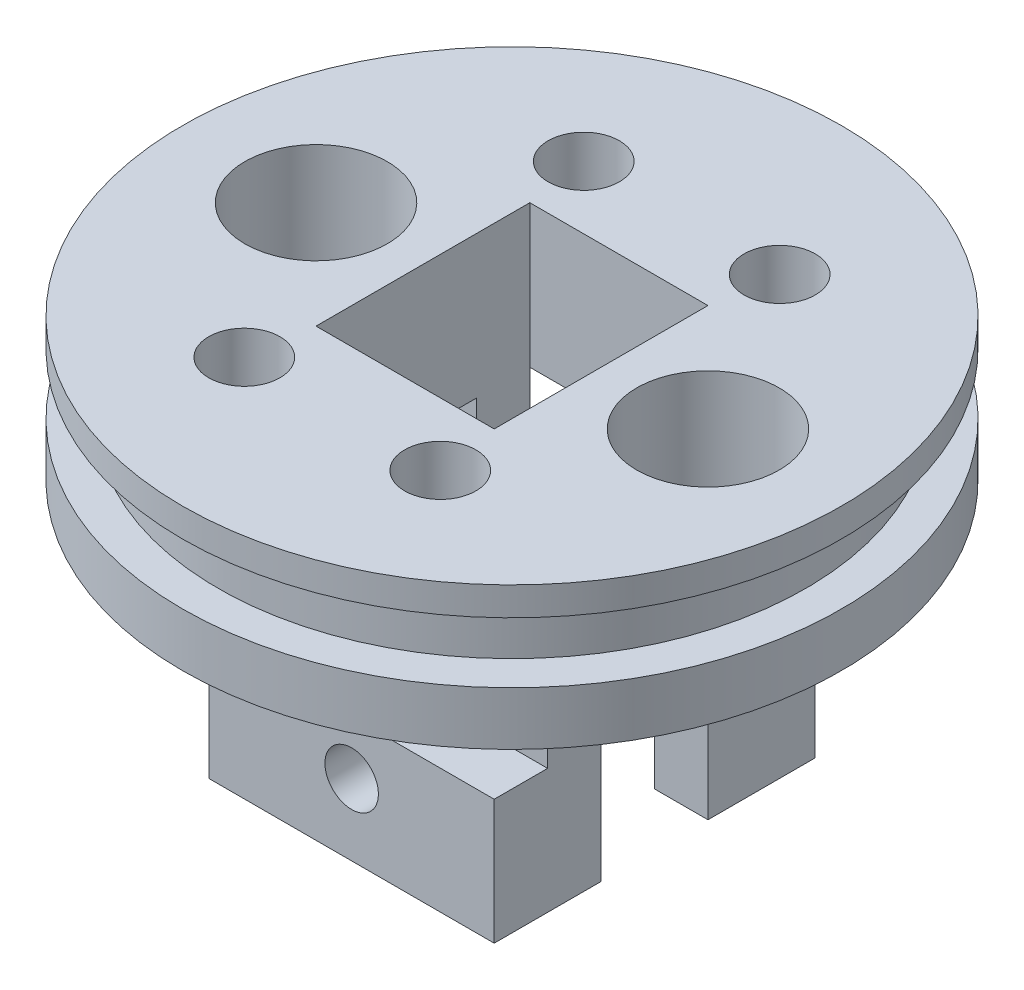
SolidWorks part; units mm, degrees
ref_plane "前视基准面" through (0, 0, 0) normal (0, 0, 1) x (1, 0, 0)
ref_plane "上视基准面" through (0, 0, 0) normal (0, 1, 0) x (1, 0, 0)
ref_plane "右视基准面" through (0, 0, 0) normal (1, 0, 0) x (0, 0, -1)
sketch "草图1" plane through (0, 0, 0) normal (0, 1, 0) x (1, 0, 0)
  circle A0 centre (0, 0) radius 11
  dimension "D1" = 22
extrude "凸台-拉伸1" add sketch "草图1" along normal blind 9
sketch "草图2" plane through (0, 9, 0) normal (0, 1, 0) x (1, 0, 0)
  circle A0 centre (-5.5, 0) radius 1
  circle A1 centre (5.5, 0) radius 1
  dimension "D1" = 2
  dimension "D2" = 2
  dimension "D3" = 11
  dimension "D4" = 5.5
extrude "切除-拉伸1" cut sketch "草图2" against normal blind 10
sketch "草图3" plane through (0, 0, 0) normal (0, -1, 0) x (1, 0, 0)
  circle A0 centre (0, 0) radius 9.25
  circle A1 centre (0, 0) radius 16.5491
  dimension "D1" = 18.5
extrude "切除-拉伸2" cut sketch "草图3" against normal blind 7
sketch "草图4" plane through (0, 0, 0) normal (0, 0, 1) x (1, 0, 0)
  line L0 (-9.25, 7) -> (-9.25, 0) construction
  line L1 (-10.25, 6.3) -> (-8.25, 6.3)
  line L2 (-10.25, 6.3) -> (-10.25, 4.6)
  line L3 (-10.25, 4.6) -> (-8.25, 4.6)
  line L4 (-8.25, 6.3) -> (-8.25, 4.6)
  line L5 (-10.25, 6.3) -> (-8.25, 4.6) construction
  line L6 (-10.25, 4.6) -> (-8.25, 6.3) construction
  line L7 (-9.25, 0) -> (9.25, 0) construction
  line L8 (-10.25, 3.2) -> (-8.25, 3.2)
  line L9 (-10.25, 3.2) -> (-10.25, 1.5)
  line L10 (-10.25, 1.5) -> (-8.25, 1.5)
  line L11 (-8.25, 3.2) -> (-8.25, 1.5)
  line L12 (-10.25, 3.2) -> (-8.25, 1.5) construction
  line L13 (-10.25, 1.5) -> (-8.25, 3.2) construction
  line L14 (0, 0) -> (0, 12.2991) construction
  point P0 (-9.25, 5.45)
  point P7 (-9.25, 2.35)
  dimension "D1" = 1.7
  dimension "D2" = 1.7
  dimension "D3" = 1.5
  dimension "D4" = 1.4
  dimension "D5" = 2
  dimension "D6" = 2
revolve "切除-旋转1" cut sketch "草图4" angle 360 about L14
sketch "草图5" plane through (0, 0, 0) normal (0, -1, 0) x (1, 0, 0)
  line L1 (-2.5, 3) -> (2.5, 3)
  line L2 (-2.5, 3) -> (-2.5, -3)
  line L3 (-2.5, -3) -> (2.5, -3)
  line L4 (2.5, 3) -> (2.5, -3)
  line L5 (-2.5, 3) -> (2.5, -3) construction
  line L6 (-2.5, -3) -> (2.5, 3) construction
  point P0 (0, 0)
  dimension "D1" = 6
  dimension "D2" = 5
extrude "切除-拉伸3" cut sketch "草图5" against normal blind 7
sketch "草图6" plane through (0, 9, 0) normal (0, 1, 0) x (1, 0, 0)
  circle A0 centre (0, 0) radius 1.4
  dimension "D1" = 2.8
extrude "切除-拉伸4" cut sketch "草图6" against normal blind 7
sketch "草图7" plane through (0, 9, 0) normal (0, 1, 0) x (1, 0, 0)
  circle A0 centre (-5.5, 0) radius 1.25
  circle A1 centre (5.5, 0) radius 1.25
  dimension "D1" = 2.5
  dimension "D2" = 2.5
extrude "切除-拉伸5" [suppressed] cut sketch "草图7" against normal blind 2.5
pattern_circular "阵列(圆周)1" count 3 every 60 about axis through (0, 0, 0) along (0, 1, 0) of "切除-拉伸1"
sketch "草图8" plane through (0, 0, 0) normal (0, -1, 0) x (1, 0, 0)
  circle A0 centre (-5.5, 0) radius 1.25
  circle A1 centre (5.5, 0) radius 1.25
  dimension "D1" = 2.5
  dimension "D2" = 2.5
extrude "切除-拉伸6" [suppressed] cut sketch "草图8" against normal blind 1.5
sketch "草图9" plane through (0, 0, 0) normal (0, -1, 0) x (1, 0, 0)
  line L0 (-2.5, 3) -> (-2.5, -3) construction
  line L1 (2.5, 3) -> (-2.5, 3) construction
  line L2 (2.5, -3) -> (2.5, 3) construction
  line L4 (-2.5, -3) -> (2.5, -3) construction
  line L5 (-2.5, -3) -> (2.5, -3)
  line L6 (2.5, -3) -> (2.5, 3)
  line L7 (2.5, 3) -> (-2.5, 3)
  line L8 (-2.5, 3) -> (-2.5, -3)
  line L9 (3.5, 4) -> (-3.5, 4)
  line L10 (-3.5, 4) -> (-3.5, -4)
  line L11 (-3.5, -4) -> (3.5, -4)
  line L12 (3.5, -4) -> (3.5, 4)
  circle A1 centre (0, 0) radius 9.25
  circle A10 centre (0, 0) radius 9.25
  line M5 (-2.5, 3) -> (2.5, 3)
  line M6 (2.5, 3) -> (2.5, -3)
  line M7 (2.5, -3) -> (-2.5, -3)
  line M8 (-2.5, -3) -> (-2.5, 3)
  dimension "D1" = 0
  dimension "D2" = 1
extrude "切除-拉伸7" [suppressed] cut sketch "草图9" against normal blind 2 contours L11 L12 L9 L10 M8 M5 M6 M7
chamfer "倒角1" [suppressed] distance 0.5 angle 45
sketch "草图10" plane through (0, 9, 0) normal (0, 1, 0) x (1, 0, 0)
  circle A0 centre (0, 0) radius 17.7553
extrude "切除-拉伸8" cut sketch "草图10" against normal blind 5
sketch "草图11" plane through (0, 4, 0) normal (0, 1, 0) x (1, 0, 0)
  circle A0 centre (-5.5, 0) radius 2
  circle A1 centre (5.5, 0) radius 2
  dimension "D1" = 4
  dimension "D2" = 4
extrude "切除-拉伸9" cut sketch "草图11" against normal blind 3
sketch "草图12" plane through (0, 0, 0) normal (0, -1, 0) x (1, 0, 0)
  line L1 (-2.5, 3) -> (2.5, 3)
  line L2 (-2.5, 3) -> (-2.5, 5)
  line L3 (-2.5, 5) -> (2.5, 5)
  line L4 (2.5, 3) -> (2.5, 5)
  line L5 (-2.5, -3) -> (2.5, -3)
  line L6 (-2.5, -3) -> (-2.5, -5)
  line L7 (-2.5, -5) -> (2.5, -5)
  line L8 (2.5, -3) -> (2.5, -5)
  line L9 (-2.5, 3) -> (-4, 3)
  line L10 (-2.5, 3) -> (-2.5, 1.5)
  line L11 (-2.5, 1.5) -> (-4, 1.5)
  line L12 (-4, 3) -> (-4, 1.5)
  line L13 (2.5, 3) -> (4, 3)
  line L14 (2.5, 3) -> (2.5, 1.5)
  line L15 (2.5, 1.5) -> (4, 1.5)
  line L16 (4, 3) -> (4, 1.5)
  line L17 (2.5, -3) -> (4, -3)
  line L18 (2.5, -3) -> (2.5, -1.5)
  line L19 (2.5, -1.5) -> (4, -1.5)
  line L20 (4, -3) -> (4, -1.5)
  line L21 (-2.5, -3) -> (-4, -3)
  line L22 (-2.5, -3) -> (-2.5, -1.5)
  line L23 (-2.5, -1.5) -> (-4, -1.5)
  line L24 (-4, -3) -> (-4, -1.5)
  line M12 (2.5, 3) -> (2.5, -3)
  line M14 (-2.5, -3) -> (-2.5, 3)
  dimension "D1" = 5
  dimension "D2" = 5
  dimension "D3" = 2
  dimension "D4" = 2
  dimension "D5" = 1.5
  dimension "D6" = 1.5
extrude "凸台-拉伸2" add sketch "草图12" along normal blind 3.5 contours L9 L12 L11 M14 | L16 L13 L15 M12 | L17 L20 L19 M12 | L24 L21 L23 M14
sketch "草图14" plane through (0, -3.5, 0) normal (0, -1, 0) x (1, 0, 0)
  line L1 (-4, 1.5) -> (4, 1.5)
  line L2 (-4, 1.5) -> (-4, 4.5)
  line L3 (-4, 4.5) -> (4, 4.5)
  line L4 (4, 1.5) -> (4, 4.5)
  line L5 (-4, -1.5) -> (4, -1.5)
  line L6 (-4, -1.5) -> (-4, -4.5)
  line L7 (-4, -4.5) -> (4, -4.5)
  line L8 (4, -1.5) -> (4, -4.5)
  line L9 (-2.5, 3) -> (2.5, 3)
  line L10 (-2.5, 3) -> (-2.5, -3)
  line L11 (-2.5, -3) -> (2.5, -3)
  line L12 (2.5, 3) -> (2.5, -3)
  line M6 (-2.5, 3) -> (-4, 3)
  line M7 (-4, 3) -> (-4, 1.5)
  line M8 (-4, 1.5) -> (-2.5, 1.5)
  line M9 (-2.5, 1.5) -> (-2.5, 3)
  dimension "D1" = 3
  dimension "D2" = 3
extrude "凸台-拉伸3" add sketch "草图14" along normal blind 3.5 contours L9 L12 L1 L4 L3 L2 M6 | M9 M6 M7 M8 | L5 L12 L11 L10 L6 L7 L8
sketch "草图13" plane through (0, 0, 4.5) normal (0, 0, -1) x (-1, 0, 0)
  line L1 (4, -7) -> (-4, -7) construction
  circle A0 centre (0, -5) radius 0.75
  dimension "D1" = 1.5
  dimension "D2" = 2
extrude "切除-拉伸11" cut sketch "草图13" along normal through all
